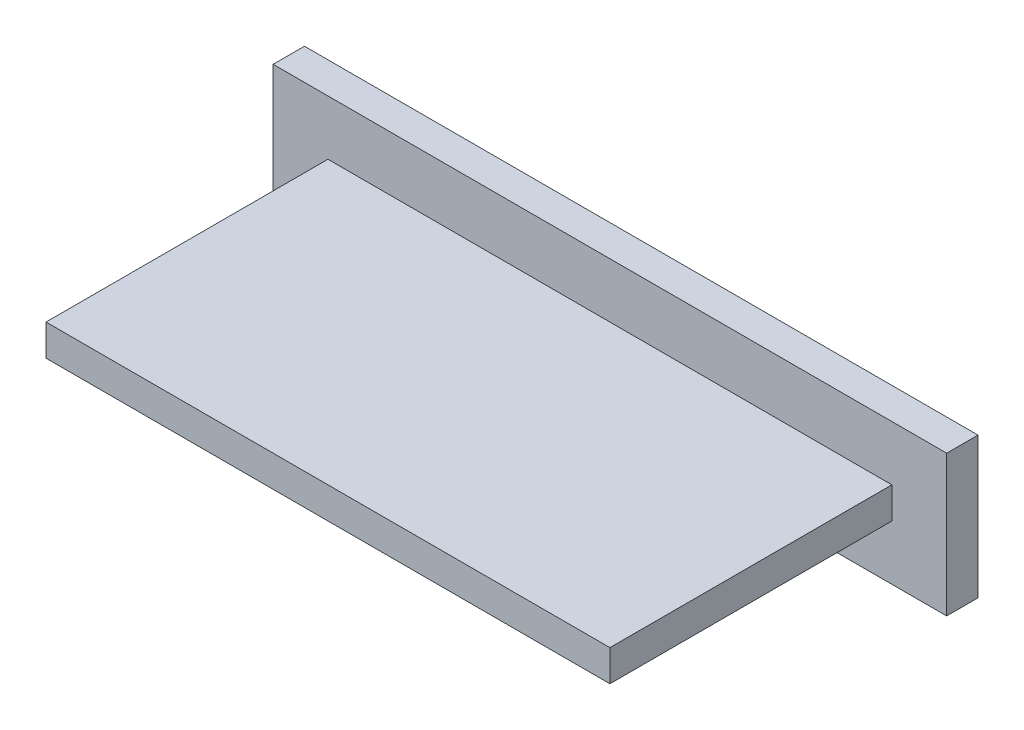
SolidWorks part; units mm, degrees
ref_plane "Alzado" through (0, 0, 0) normal (0, 0, 1) x (1, 0, 0)
ref_plane "Planta" through (0, 0, 0) normal (0, 1, 0) x (1, 0, 0)
ref_plane "Vista lateral" through (0, 0, 0) normal (1, 0, 0) x (0, 0, -1)
sketch "Croquis1" plane through (0, 0, 0) normal (0, 0, 1) x (1, 0, 0)
  line L1 (0, 0) -> (86, 0)
  line L2 (0, 0) -> (0, -18)
  line L3 (0, -18) -> (86, -18)
  line L4 (86, 0) -> (86, -18)
  dimension "D1" = 86
  dimension "D2" = 18
extrude "Saliente-Extruir1" add sketch "Croquis1" along normal blind 4
sketch "Croquis2" plane through (0, 0, 4) normal (0, 0, 1) x (1, 0, 0)
  line L1 (86, 0) -> (0, 0) construction
  line L8 (86, -18) -> (86, 0) construction
  line L11 (7, -7) -> (79, -7)
  line L12 (79, -7) -> (79, -11)
  line L13 (79, -11) -> (7, -11)
  line L14 (7, -11) -> (7, -7)
  dimension "D1" = 4
  dimension "D2" = 72
  dimension "D3" = 7
  dimension "D4" = 7
extrude "Saliente-Extruir2" add sketch "Croquis2" along normal blind 36
sketch "Croquis3" plane through (0, 0, 4) normal (0, 0, 1) x (1, 0, 0)
  line L0 (79, -7) -> (86, 0) construction
  line L1 (79, -11) -> (86, -18) construction
  line L2 (0, 0) -> (7, -7) construction
  line L3 (7, -11) -> (0, -18) construction
  circle A0 centre (3.5, -3.5) radius 1.5
  circle A1 centre (3.5, -14.5) radius 1.5
  circle A2 centre (82.5, -3.5) radius 1.5
  circle A3 centre (82.5, -14.5) radius 1.5
  dimension "D1" = 3
  dimension "D2" = 3
  dimension "D3" = 3
  dimension "D4" = 3
